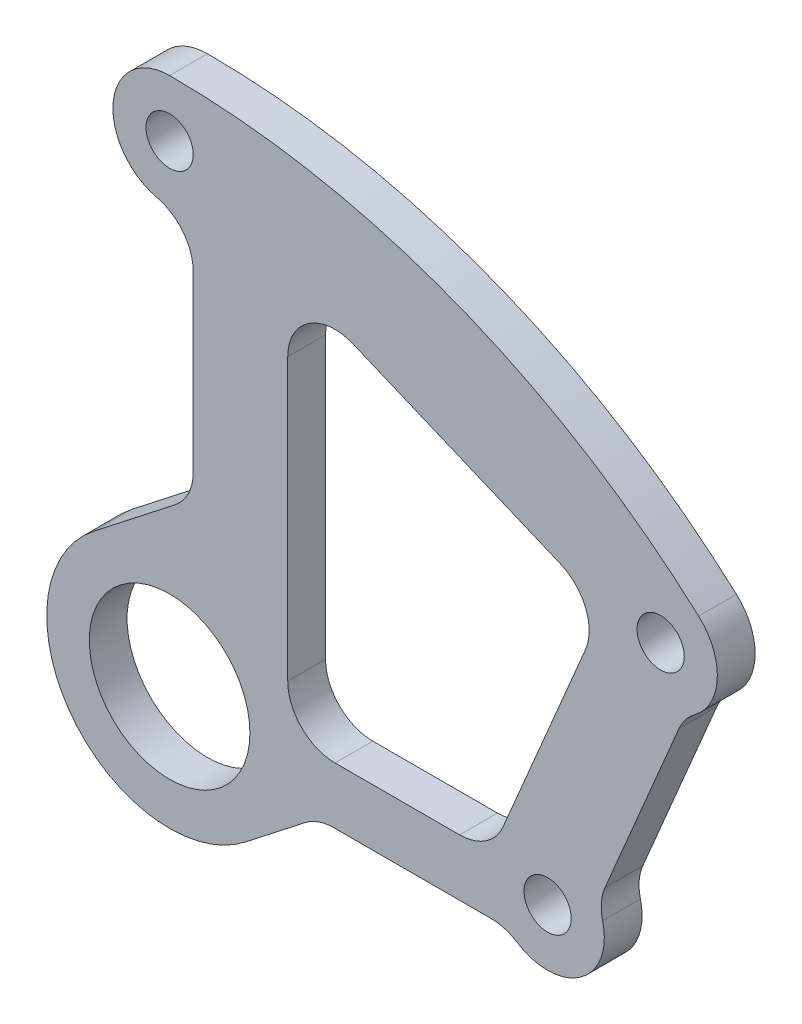
SolidWorks part; units mm, degrees
other "Weld Folder"
ref_plane "Płaszczyzna przednia" through (0, 0, 0) normal (0, 0, 1) x (1, 0, 0)
ref_plane "Płaszczyzna górna" through (0, 0, 0) normal (0, 1, 0) x (1, 0, 0)
ref_plane "Płaszczyzna prawa" through (0, 0, 0) normal (1, 0, 0) x (0, 0, -1)
sketch "Sketch1" plane through (0, 0, 0) normal (0, 0, 1) x (1, 0, 0)
  line L0 (103.923, 60) -> (0, 0) construction
  line L1 (0, 0) -> (80, 0) construction
  line L3 (5, 78.5757) -> (5, 41.7782)
  line L4 (-16.0072, 20.4883) -> (16.0072, -20.4883) construction
  line L5 (1.1566, 33.8981) -> (-16.0072, 20.4883)
  line L6 (25, 72.9761) -> (25, 13.5147)
  line L7 (35, 3.5147) -> (61.3754, 3.5147)
  line L8 (70.5836, 9.6148) -> (88.0061, 50.7516)
  line L9 (82.6576, 63.8766) -> (38.8597, 82.2012)
  line L10 (80, 0) -> (76.4645, 3.5355) construction
  line L11 (80, 0) -> (71.5147, -8.4853) construction
  line L12 (107.8062, 46.2189) -> (92.1379, 9.224)
  line L13 (68.0713, -8.4853) -> (34.8136, -8.4853)
  line L14 (16.0072, -20.4883) -> (28.657, -10.6052)
  line L15 (5, 88) -> (5, 100) construction
  line L17 (5, 78.5757) -> (5, 88) construction
  circle A0 centre (0, 0) radius 17
  circle A1 centre (0, 100) radius 5
  circle A2 centre (80, 0) radius 5
  circle A3 centre (103.923, 60) radius 5
  arc A4 (0, 112) -> (-2.7273, 88.314) centre (0, 100) ccw
  arc A5 (-16.0072, 20.4883) -> (16.0072, -20.4883) centre (0, 0) ccw
  arc A6 (91.6433, 2.9041) -> (73.4934, -10.0829) centre (80, 0) cw
  arc A7 (111.0638, 50.3558) -> (111.9687, 68.9032) centre (103.923, 60) ccw
  arc A8 (0, 112) -> (111.9687, 68.9032) centre (0, -55) cw
  arc A9 (5, 78.5757) -> (-2.7273, 88.314) centre (-5, 78.5757) ccw
  arc A10 (34.8136, -8.4853) -> (28.657, -10.6052) centre (34.8136, -18.4853) ccw
  arc A11 (73.4934, -10.0829) -> (68.0713, -8.4853) centre (68.0713, -18.4853) ccw
  arc A12 (91.6433, 2.9041) -> (92.1379, 9.224) centre (101.346, 5.3241) cw
  arc A13 (111.0638, 50.3558) -> (107.8062, 46.2189) centre (117.0144, 42.319) ccw
  arc A14 (25, 72.9761) -> (38.8597, 82.2012) centre (35, 72.9761) cw
  arc A15 (88.0061, 50.7516) -> (82.6576, 63.8766) centre (78.7979, 54.6515) ccw
  arc A16 (61.3754, 3.5147) -> (70.5836, 9.6148) centre (61.3754, 13.5147) ccw
  arc A17 (35, 3.5147) -> (25, 13.5147) centre (35, 13.5147) cw
  arc A18 (1.1566, 33.8981) -> (5, 41.7782) centre (-5, 41.7782) ccw
  point P42 (25, 88)
  point P45 (91.923, 60)
  point P48 (68, 3.5147)
  dimension "D1" = 10
  dimension "D2" = 10
  dimension "D3" = 10
  dimension "D4" = 120
  dimension "34" = 34
  dimension "D10" = 9
  dimension "D11" = 7
  dimension "D12" = 7
  dimension "D13" = 7
  dimension "D21" = 10
  dimension "D23" = 10
  dimension "D5" = 128
  dimension "D6" = 100
  dimension "D7" = 30
  dimension "D8" = 80
  dimension "D14" = 90
  dimension "D15" = 45
  dimension "D16" = 12
  dimension "D17" = 20
  dimension "D18" = 20
  dimension "D19" = 12
  dimension "D20" = 12
  dimension "D22" = 12
extrude "Boss-Extrude1" add sketch "Sketch1" along normal mid plane 8
equation "\"d\"= 10'dziura pod pushrody"
equation "\"g\"= 7'grubość dookoła otworów"
equation "\"D4\"=28"
